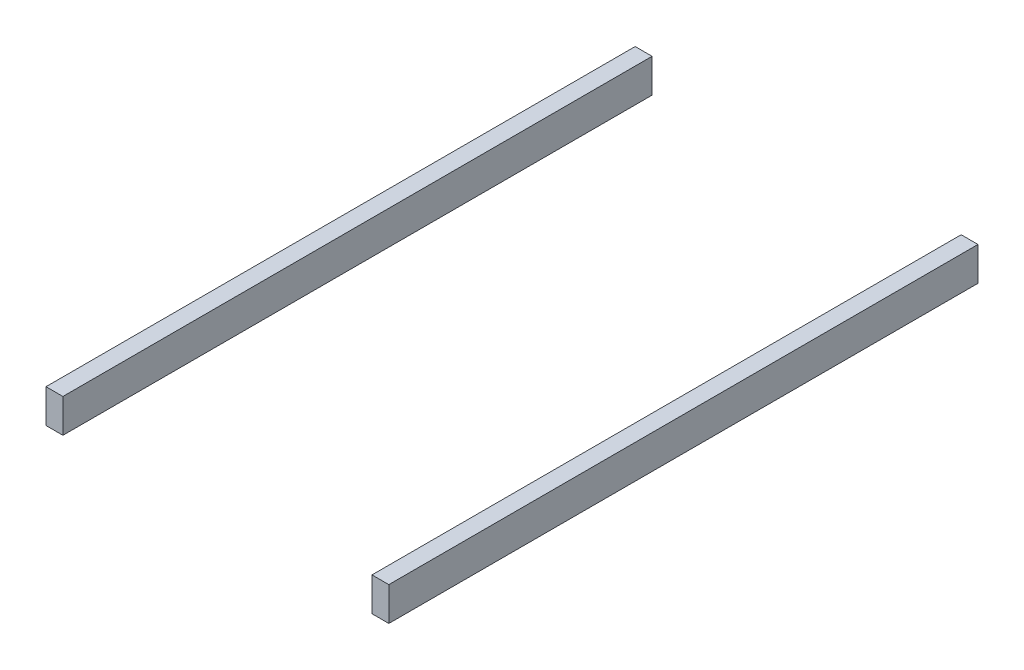
SolidWorks part; units mm, degrees
ref_plane "Front Plane" through (0, 0, 0) normal (0, 0, 1) x (1, 0, 0)
ref_plane "Top Plane" through (0, 0, 0) normal (0, 1, 0) x (1, 0, 0)
ref_plane "Right Plane" through (0, 0, 0) normal (1, 0, 0) x (0, 0, -1)
sketch "Sketch1" plane through (0, 0, 0) normal (0, 0, 1) x (1, 0, 0)
  line L0 (1900.945, 39.6673) -> (2000.945, 39.6673)
  line L1 (-35.5638, 39.6673) -> (64.945, 39.6673)
  line L2 (-35.5638, 39.6673) -> (-35.5638, -160.3327)
  line L3 (-35.5638, -160.3327) -> (64.945, -160.3327)
  line L4 (64.945, 39.6673) -> (64.945, -160.3327)
  line L5 (1900.945, 39.6673) -> (1900.945, -160.3327)
  line L6 (1900.945, -160.3327) -> (2000.945, -160.3327)
  line L7 (2000.945, 39.6673) -> (2000.945, -160.3327)
  line L8 (64.945, 39.6673) -> (1901.1993, 39.6673) construction
  line L9 (1901.1993, 569.6673) -> (1901.1993, -690.3327) construction
  dimension "D1" = 1836
extrude "Boss-Extrude1" add sketch "Sketch1" along normal blind 3500
